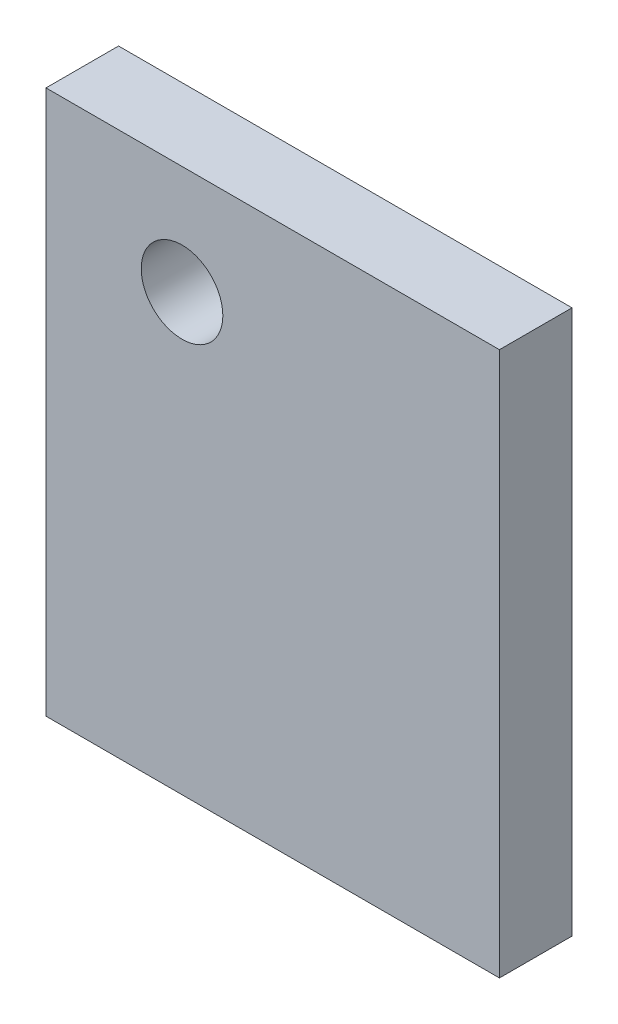
SolidWorks part; units mm, degrees
ref_plane "Front Plane" through (0, 0, 0) normal (0, 0, 1) x (1, 0, 0)
ref_plane "Top Plane" through (0, 0, 0) normal (0, 1, 0) x (1, 0, 0)
ref_plane "Right Plane" through (0, 0, 0) normal (1, 0, 0) x (0, 0, -1)
sketch "Sketch1" plane through (0, 0, 0) normal (0, 0, 1) x (1, 0, 0)
  line L1 (-25, -30) -> (25, -30)
  line L2 (-25, -30) -> (-25, 30)
  line L3 (-25, 30) -> (25, 30)
  line L4 (25, -30) -> (25, 30)
  line L5 (-25, -30) -> (25, 30) construction
  line L6 (-25, 30) -> (25, -30) construction
  circle A0 centre (-10, 18) radius 4.5
  point P0 (0, 0)
  dimension "D3" = 12
  dimension "D5" = 9
  dimension "D1" = 60
  dimension "D2" = 50
  dimension "D4" = 15
extrude "Boss-Extrude1" add sketch "Sketch1" along normal blind 8
